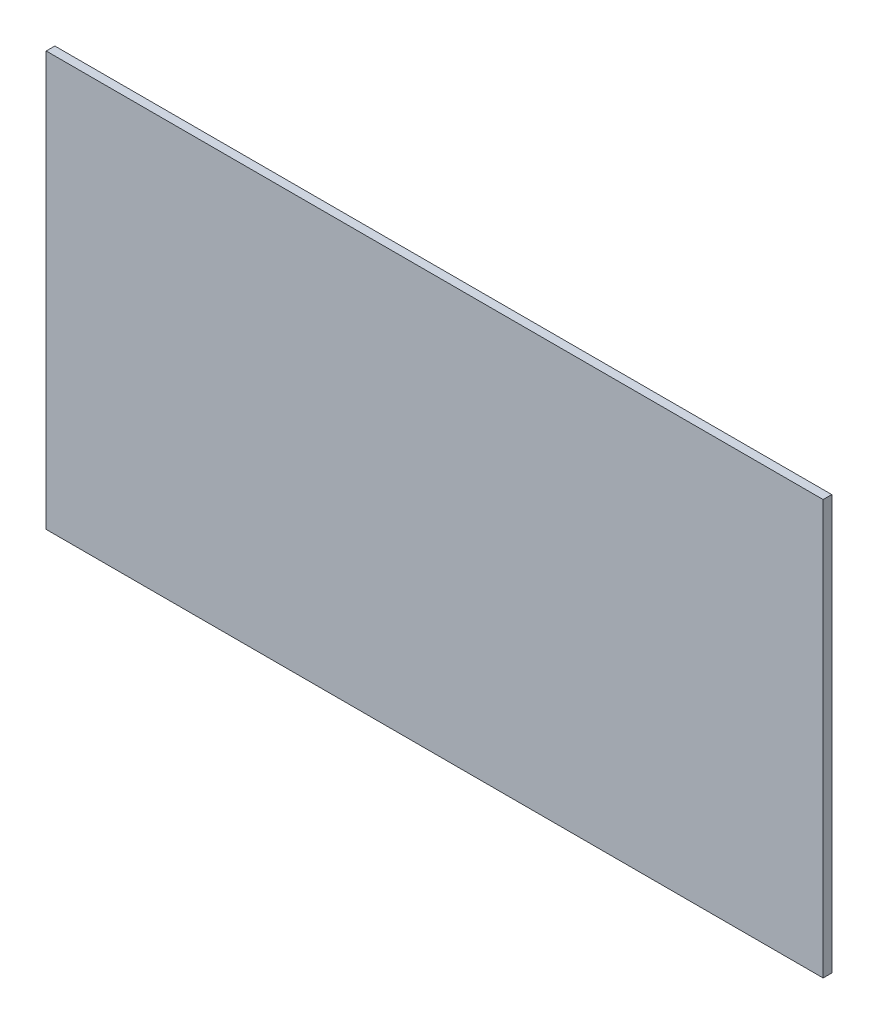
SolidWorks part; units mm, degrees
material "Pine"
ref_plane "Front Plane" through (0, 0, 0) normal (0, 0, 1) x (1, 0, 0)
ref_plane "Top Plane" through (0, 0, 0) normal (0, 1, 0) x (1, 0, 0)
ref_plane "Right Plane" through (0, 0, 0) normal (1, 0, 0) x (0, 0, -1)
sketch "Sketch1" plane through (0, 0, 0) normal (0, 0, 1) x (1, 0, 0)
  line L0 (571.5, -812.8) -> (571.5, 0) construction
  line L1 (-571.5, -723.9) -> (571.5, -723.9)
  line L2 (-571.5, -723.9) -> (-571.5, -114.3)
  line L3 (-571.5, -114.3) -> (571.5, -114.3)
  line L4 (571.5, -723.9) -> (571.5, -114.3)
  line L5 (0, -114.3) -> (0, -723.9) construction
  line L6 (-571.5, -419.1) -> (571.5, -419.1) construction
  point P268 (0, -419.1)
  dimension "D1" = 609.6
extrude "Boss-Extrude1" add sketch "Sketch1" along normal blind 12.7
